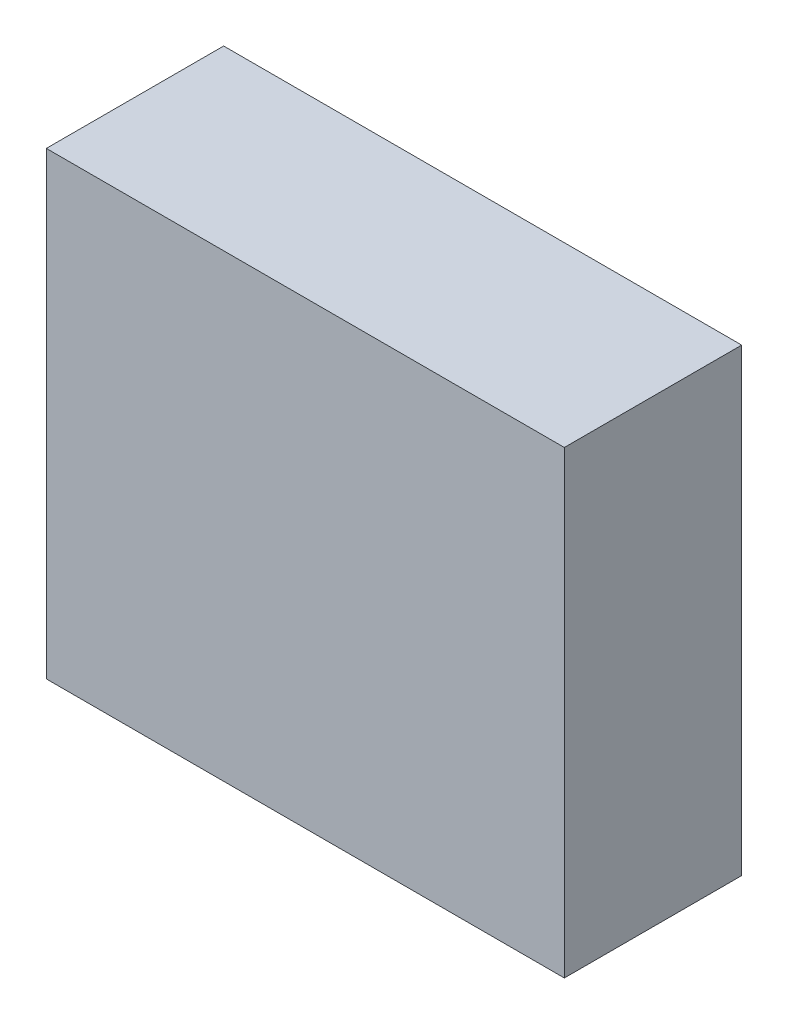
SolidWorks part; units mm, degrees
ref_plane "Front Plane" through (0, 0, 0) normal (0, 0, 1) x (1, 0, 0)
ref_plane "Top Plane" through (0, 0, 0) normal (0, 1, 0) x (1, 0, 0)
ref_plane "Right Plane" through (0, 0, 0) normal (1, 0, 0) x (0, 0, -1)
sketch "Sketch1" plane through (0, 0, 0) normal (0, 0, 1) x (1, 0, 0)
  line L0 (-1.4224, 1.2954) -> (1.4986, 1.2954)
  line L1 (1.4986, 1.2954) -> (1.4986, -1.2954)
  line L2 (1.4986, -1.2954) -> (-1.4224, -1.2954)
  line L3 (-1.4224, -1.2954) -> (-1.4224, 1.2954)
extrude "Component_Outline" add sketch "Sketch1" along normal blind 1 separate body
sketch3d "3DSketch1"
  line L0 (0, 0, 0) -> (1, 0, 0)
  line L1 (0, 0, 0) -> (0, 1, 0)
  line L2 (0, 0, 0) -> (0, 0, 1)
  point P0 (0, 0, 0)
